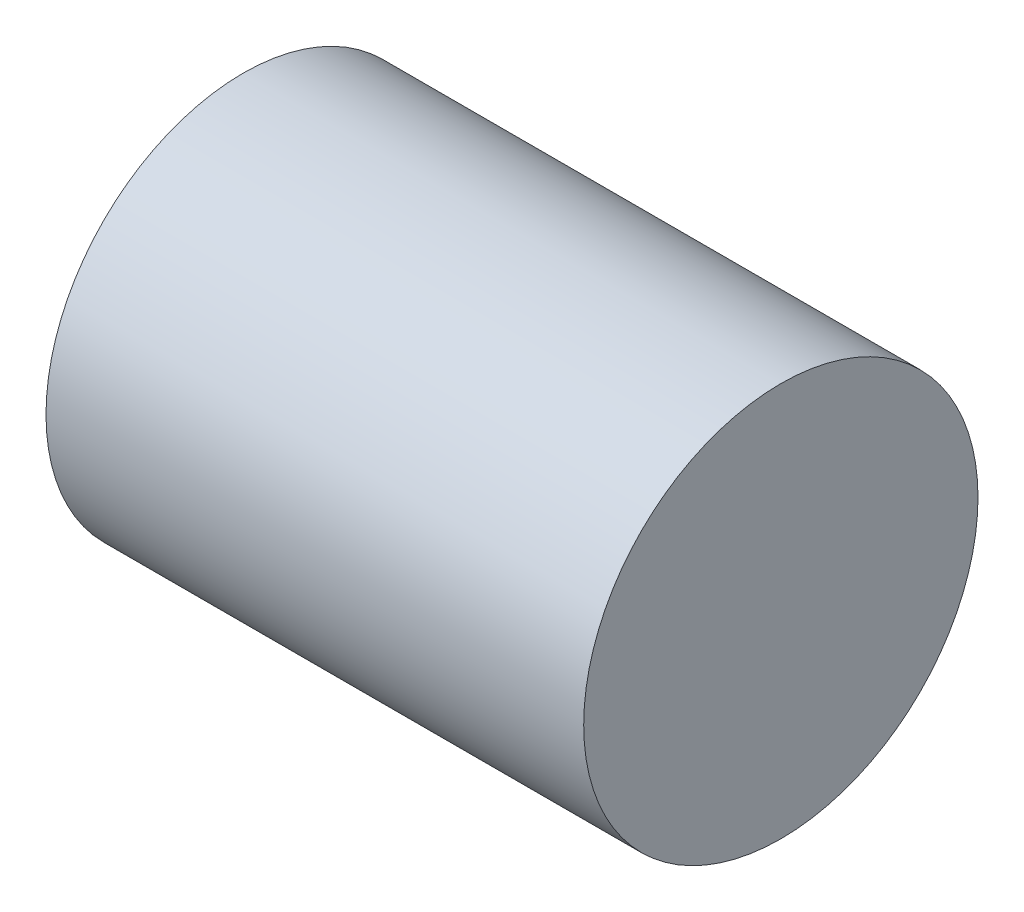
SolidWorks part; units mm, degrees
material "ASTM A500 Grade C"
ref_plane "Front Plane" through (0, 0, 0) normal (1, 0, 0) x (0, 1, 0)
ref_plane "Top Plane" through (0, 0, 0) normal (0, 0, 1) x (0, 1, 0)
ref_plane "Right Plane" through (0, 0, 0) normal (0, 1, 0) x (-1, 0, 0)
sketch "Sketch1" plane through (0, 0, 0) normal (1, 0, 0) x (0, 1, 0)
  circle A0 centre (0, 0) radius 5.5
  dimension "D1" = 11
extrude "Boss-Extrude1" add sketch "Sketch1" along normal blind 15 contours A0
